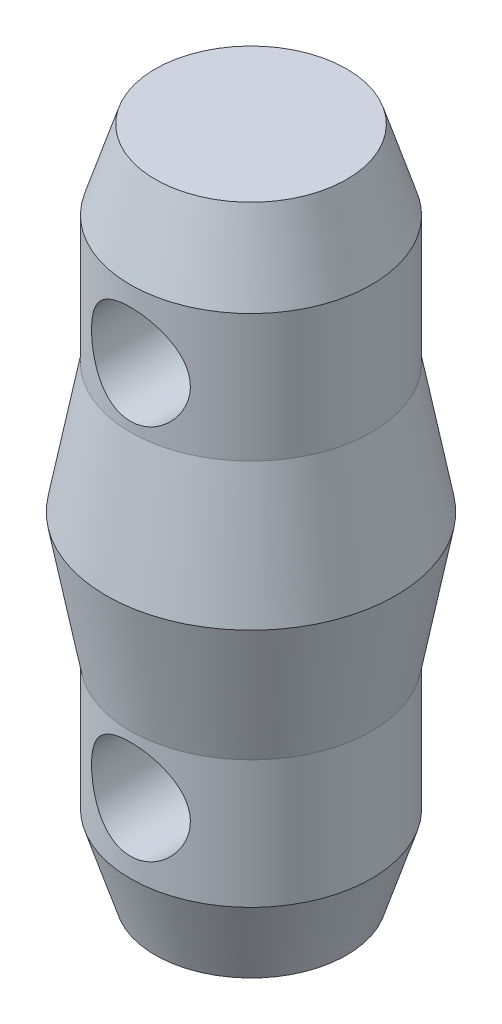
SolidWorks part; units mm, degrees
material "6061-T6 (SS)"
ref_plane "Front" through (0, 0, 0) normal (0, 0, 1) x (1, 0, 0)
ref_plane "Top" through (0, 0, 0) normal (0, 1, 0) x (1, 0, 0)
ref_plane "Right" through (0, 0, 0) normal (1, 0, 0) x (0, 0, -1)
sketch "Sketch1" plane through (0, 0, 0) normal (0, 0, 1) x (1, 0, 0)
  line L0 (0, 0) -> (0, 40.0685)
  line L1 (0, -50) -> (0, 50) construction
  line L2 (0, 40.0685) -> (11.4173, 40.0685)
  line L3 (11.4173, 40.0685) -> (14.3891, 30.672)
  line L4 (14.3891, 30.672) -> (14.3891, 15.432)
  line L5 (14.3891, 15.432) -> (17.272, 0)
  line L6 (50, 0) -> (-50, 0) construction
  line L7 (17.272, 0) -> (0, 0)
  dimension "D1" = 17.272
  dimension "D2" = 14.3891
  dimension "D3" = 40.0685
  dimension "D4" = 11.4173
  dimension "D5" = 15.24
  dimension "D6" = 9.8552
revolve "Revolve1" add sketch "Sketch1" angle 360 about L0
sketch "Sketch2" plane through (0, 0, 0) normal (0, 0, 1) x (1, 0, 0)
  line L0 (0, 30.672) -> (0, 40.0685) construction
  line L1 (11.4173, 40.0685) -> (-11.4173, 40.0685) construction
  circle A0 centre (0, 22.4663) radius 5.8928
  dimension "D1" = 17.6022
  dimension "D2" = 11.7856
extrude "Cut-Extrude1" cut sketch "Sketch2" against normal through all and the other way through all
mirror "Mirror1" about plane through (17.272, 0, 0) normal (0, -1, 0) of "Cut-Extrude1", "Revolve1"
